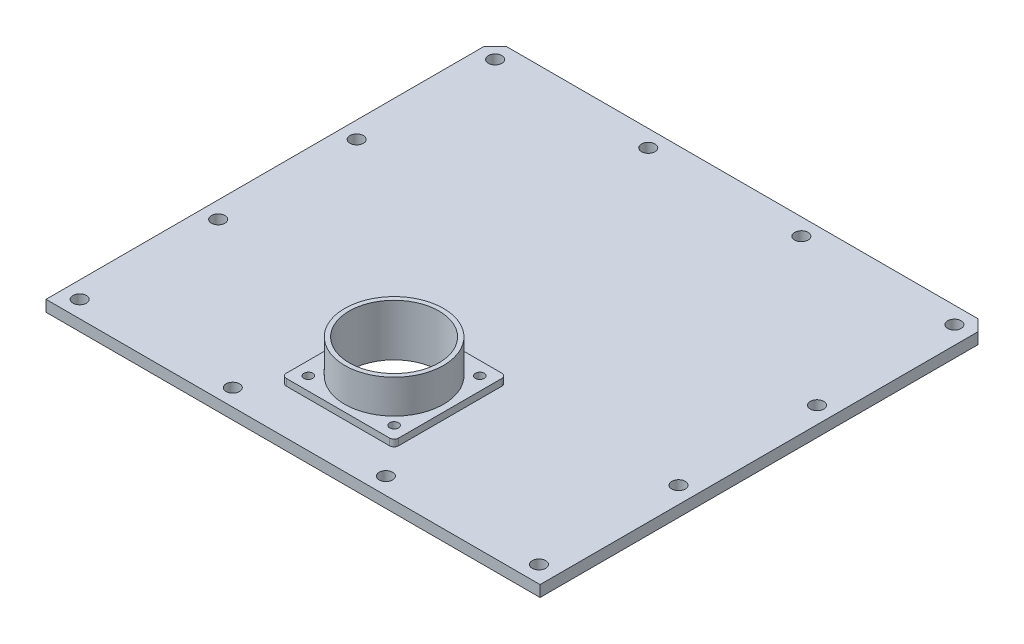
SolidWorks part; units mm, degrees
ref_plane "Спереди" through (0, 0, 0) normal (0, 0, 1) x (1, 0, 0)
ref_plane "Сверху" through (0, 0, 0) normal (0, 1, 0) x (1, 0, 0)
ref_plane "Справа" through (0, 0, 0) normal (1, 0, 0) x (0, 0, -1)
sketch "Sketch1" plane through (0, 0, 0) normal (0, 1, 0) x (1, 0, 0)
  line L0 (110, -150) -> (110, 50)
  line L1 (0, 50) -> (-110, 50)
  line L2 (-110, 50) -> (-110, -150)
  line L3 (-110, -150) -> (110, -150)
  line L4 (110, 50) -> (0, 50)
  line L5 (-110, 50) -> (-102.5, 50)
  line L6 (-102.5, 50) -> (-102.5, 42.5)
  circle A0 centre (-102.5, 42.5) radius 3
  circle A1 centre (-34.33, 42.5) radius 3
  circle A2 centre (33.84, 42.5) radius 3
  circle A3 centre (102.01, 42.5) radius 3
  circle A4 centre (-34.33, -142.5) radius 3
  circle A5 centre (33.84, -142.5) radius 3
  circle A6 centre (102.01, -142.5) radius 3
  circle A7 centre (-102.5, -142.5) radius 3
  circle A8 centre (-102.5, -19.17) radius 3
  circle A9 centre (-102.5, -80.84) radius 3
  circle A10 centre (102.5, -19.17) radius 3
  circle A11 centre (102.5, -80.84) radius 3
  circle A12 centre (102.5, 42.5) radius 3
  circle A13 centre (0, -105) radius 20
  point P8 (0, 0)
  dimension "D1" = 4
  dimension "D2" = 2
  dimension "D3" = 3
  dimension "D4" = 2
extrude "Boss-Extrude1" add sketch "Sketch1" along normal blind 5 contours L2 L3 L0 L4 L1 | A8 | A9 | A7 | A4 | A5 | A6 | A11 | A10 | A3 | A2 | A1 | A0 | A13
chamfer "Chamfer1" distance 5 angle 45 2 edges at (110, 2.5, -50) (-110, 2.5, -50)
sketch "Sketch2" plane through (0, 5, 0) normal (0, 1, 0) x (1, 0, 0)
  line L2 (0, -130) -> (-25, -130)
  line L3 (-25, -130) -> (-25, -80)
  line L4 (-25, -80) -> (25, -80)
  line L5 (25, -80) -> (25, -130)
  line L6 (25, -130) -> (0, -130)
extrude "Boss-Extrude3" add sketch "Sketch2" along normal blind 3 contours L4 L5 L6 L2 L3
sketch "Sketch3" plane through (0, 8, 0) normal (0, 1, 0) x (1, 0, 0)
  circle A2 centre (0, -105) radius 20
  circle A3 centre (0, -105) radius 22
extrude "Boss-Extrude4" add sketch "Sketch3" along normal blind 15 contours A3 | A2
fillet "Fillet2" radius 2 4 edges at (-25, 6.5, 130) (-25, 6.5, 80) (25, 6.5, 80) (25, 6.5, 130)
sketch "Sketch4" plane through (0, 0, 0) normal (0, -1, 0) x (1, 0, 0)
  line L1 (0, 130) -> (-90, 130)
  line L2 (0, 135) -> (95, 135)
  line L3 (95, 135) -> (95, -35)
  line L4 (95, -35) -> (-95, -35)
  line L5 (-95, -35) -> (-95, 135)
  line L6 (-95, 135) -> (0, 135)
  line L7 (-90, 130) -> (-90, -30)
  line L8 (-90, -30) -> (90, -30)
  line L9 (90, -30) -> (90, 130)
  line L10 (90, 130) -> (0, 130)
  point P11 (0, 0)
  circle M19 centre (0, 105) radius 20
extrude "Boss-Extrude5" add sketch "Sketch4" along normal blind 5 contours L6 L5 L4 L3 L2 L10 L9 L8 L7 L1 | L9 L10 L1 L7 L8 M19
sketch "Sketch6" plane through (0, 5, 0) normal (0, -1, 0) x (1, 0, 0)
  circle A0 centre (0, 105) radius 20
extrude "Cut-Extrude1" cut sketch "Sketch6" against normal blind 5
sketch "Sketch7" plane through (0, 8, 0) normal (0, 1, 0) x (1, 0, 0)
  circle A2 centre (19.0919, -124.0919) radius 2
  circle A3 centre (-19.0919, -124.0919) radius 2
  circle A4 centre (-19.0919, -85.9081) radius 2
  circle A5 centre (19.0919, -85.9081) radius 2
  point P7 (19.0919, -124.0919)
  point P13 (0, -105)
extrude "Cut-Extrude2" cut sketch "Sketch7" against normal blind 10
chamfer "Chamfer2" distance 2 angle 45 4 edges at (0, -5, -35) (95, -5, 50) (-95, -5, 50) (0, -5, 135)
